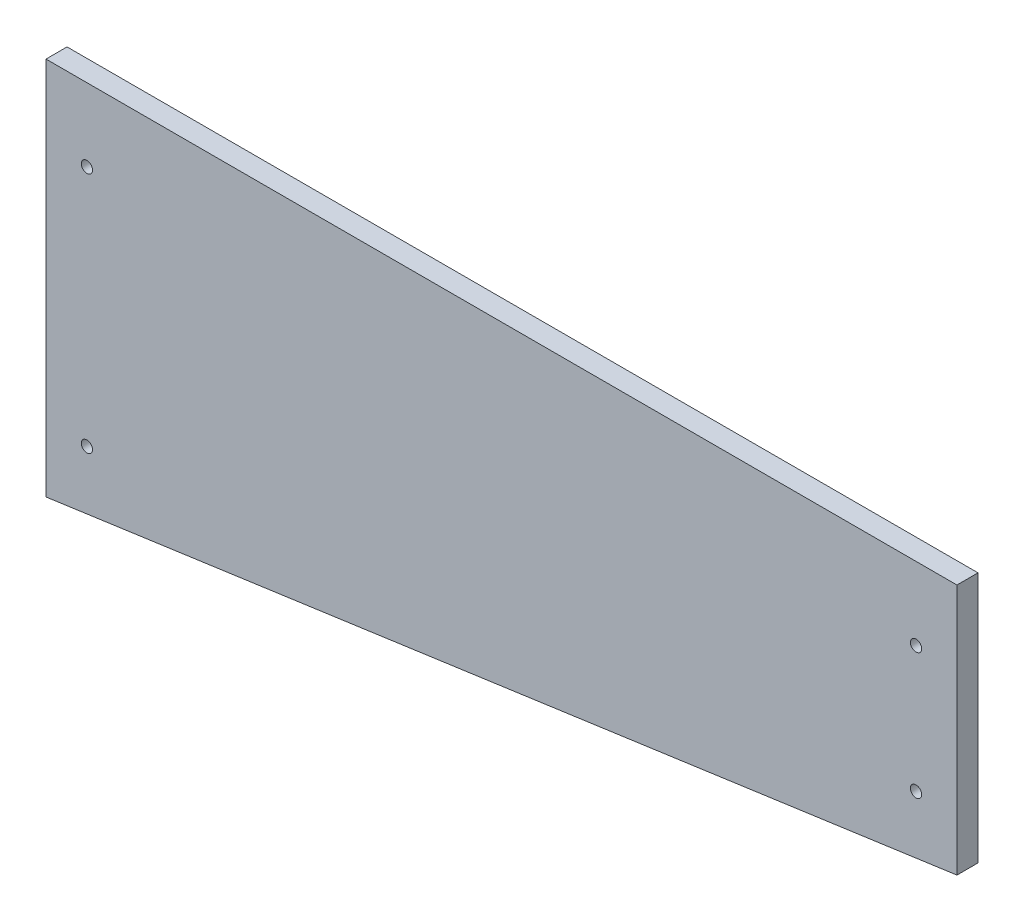
SolidWorks part; units mm, degrees
material "Acrylic (Medium-high impact)"
ref_plane "Front Plane" through (0, 0, 0) normal (0, 0, 1) x (1, 0, 0)
ref_plane "Top Plane" through (0, 0, 0) normal (0, 1, 0) x (1, 0, 0)
ref_plane "Right Plane" through (0, 0, 0) normal (1, 0, 0) x (0, 0, -1)
sketch "Sketch1" plane through (0, 0, 0) normal (0, 0, 1) x (1, 0, 0)
  line L1 (274.7772, 114.4016) -> (0, 114.4016)
  line L2 (274.7772, 114.4016) -> (274.7772, 0)
  line L3 (274.7772, 0) -> (0, 0)
  line L4 (0, 114.4016) -> (0, 0)
  line L5 (274.7772, 114.4016) -> (0, 0) construction
  line L6 (274.7772, 0) -> (0, 114.4016) construction
  point P0 (137.3886, 57.2008)
  dimension "D1" = 114.4016
  dimension "D2" = 274.7772
extrude "Boss-Extrude1" add sketch "Sketch1" along normal blind 6.35
hole_wizard "M3 Clearance Hole1" positions "Sketch2" profile "Sketch3" hole size "M3" standard "ANSI Metric" end condition through all
sketch "Sketch2" plane through (0, 0, 6.35) normal (0, 0, 1) x (1, 0, 0)
  line L0 (0, 114.4016) -> (0, 0) construction
  line L1 (274.7772, 114.4016) -> (0, 114.4016) construction
  line L2 (274.7772, 0) -> (274.7772, 114.4016) construction
  point P0 (12.3444, 92.4052)
  point P2 (12.3444, 19.3802)
  point P4 (262.4328, 54.3052)
  point P6 (262.4328, 92.4052)
  dimension "D1" = 12.3444
  dimension "D2" = 21.9964
  dimension "D3" = 12.3444
  dimension "D4" = 73.025
  dimension "D5" = 38.1
sketch "Sketch3" plane through (12.3444, 92.4052, 6.35) normal (1, 0, 0) x (0, -1, 0)
  line L0 (0, 0) -> (0, 6.35)
  line L1 (0, 6.35) -> (1.7, 6.35)
  line L2 (1.7, 6.35) -> (1.7, 0)
  line L5 (1.7, 0) -> (0, 0)
  line L11 (0, -6.35) -> (0, 107.95) construction
  dimension "Thru Hole Dia." = 3.4
  dimension "Thru Hole Depth" = 6.35
sketch "Sketch4" plane through (0, 0, 6.35) normal (0, 0, 1) x (1, 0, 0)
  line L0 (0, 114.4016) -> (0, 0) construction
  line L1 (46.99, 95.3516) -> (50.4952, 95.3516)
  line L2 (46.99, 95.3516) -> (46.99, 19.1516)
  line L3 (46.99, 19.1516) -> (50.4952, 19.1516)
  line L4 (50.4952, 95.3516) -> (50.4952, 19.1516)
  line L5 (224.282, 95.3516) -> (227.7872, 95.3516)
  line L6 (224.282, 95.3516) -> (224.282, 19.1516)
  line L7 (224.282, 19.1516) -> (227.7872, 19.1516)
  line L8 (227.7872, 95.3516) -> (227.7872, 19.1516)
  line L9 (274.7772, 0) -> (274.7772, 114.4016) construction
  line L10 (274.7772, 114.4016) -> (0, 114.4016) construction
  dimension "D1" = 3.5052
  dimension "D2" = 76.2
  dimension "D3" = 46.99
  dimension "D4" = 46.99
  dimension "D5" = 19.05
extrude "Cut-Extrude1" [suppressed] cut sketch "Sketch4" against normal through all
sketch "Sketch5" plane through (0, 0, 6.35) normal (0, 0, 1) x (1, 0, 0)
  line L0 (0, 0) -> (274.7772, 0)
  line L1 (274.7772, 0) -> (274.7772, 38.6174)
  line L2 (274.7772, 0) -> (274.7772, 114.4016) construction
  line L3 (274.7772, 38.6174) -> (0, 0)
  dimension "D1" = 8
extrude "Cut-Extrude2" cut sketch "Sketch5" against normal through all
